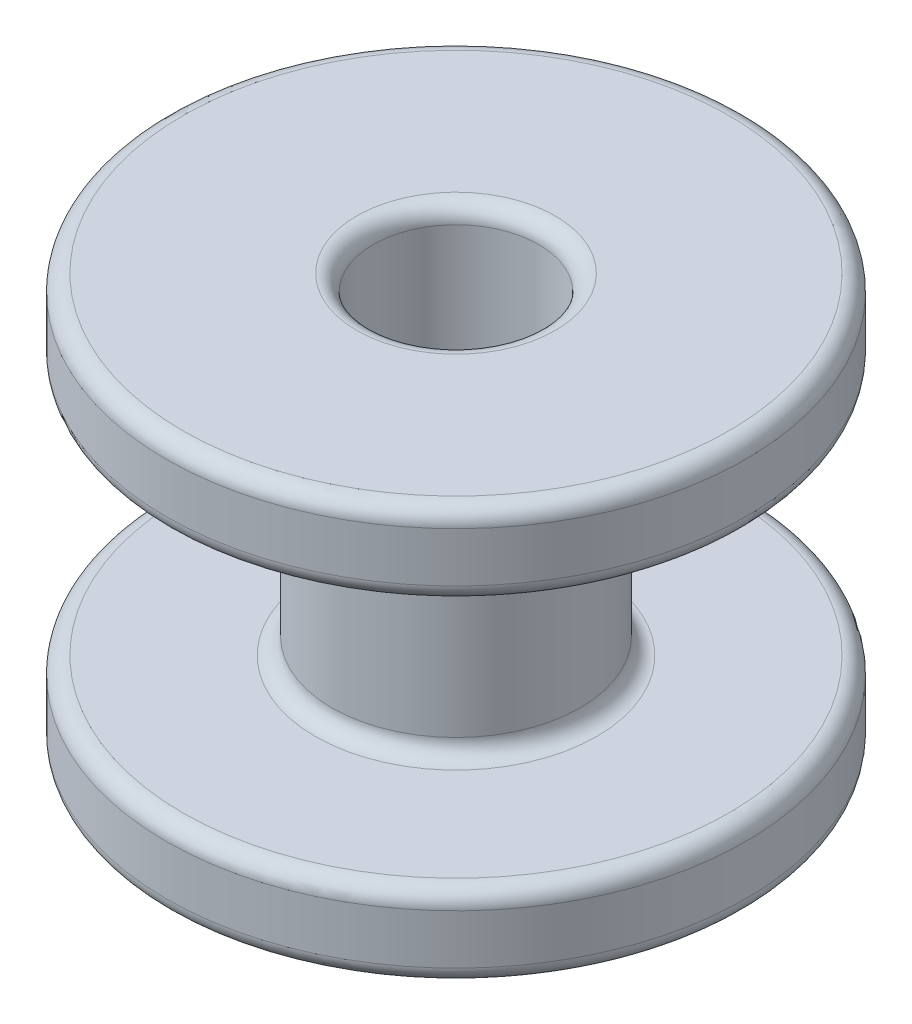
SolidWorks part; units mm, degrees
ref_plane "Front Plane" through (0, 0, 0) normal (0, 0, 1) x (1, 0, 0)
ref_plane "Top Plane" through (0, 0, 0) normal (0, 1, 0) x (1, 0, 0)
ref_plane "Right Plane" through (0, 0, 0) normal (1, 0, 0) x (0, 0, -1)
sketch "Sketch1" plane through (0, 0, 0) normal (0, 1, 0) x (1, 0, 0)
  circle A0 centre (0, 0) radius 1.5
  dimension "D1" = 3
extrude "Boss-Extrude1" add sketch "Sketch1" along normal blind 1.5
sketch "Sketch2" plane through (0, 1.5, 0) normal (0, 1, 0) x (1, 0, 0)
  circle A0 centre (0, 0) radius 3.5
  dimension "D1" = 7
extrude "Boss-Extrude2" add sketch "Sketch2" along normal blind 1
sketch "Sketch3" plane through (0, 2.5, 0) normal (0, 1, 0) x (1, 0, 0)
  circle A0 centre (0, 0) radius 1
  dimension "D1" = 2
extrude "Cut-Extrude1" cut sketch "Sketch3" against normal through all
fillet "Fillet1" radius 0.2 4 edges at (0, 2.5, 1) (0, 0, 1) (0, 1.5, 3.5) (0, 2.5, 3.5)
fillet "Fillet2" radius 0.2 1 edges at (0, 1.5, 1.5)
mirror "Mirror1" about plane through (0, 0, 0) normal (0, 1, 0) of bodies 103
